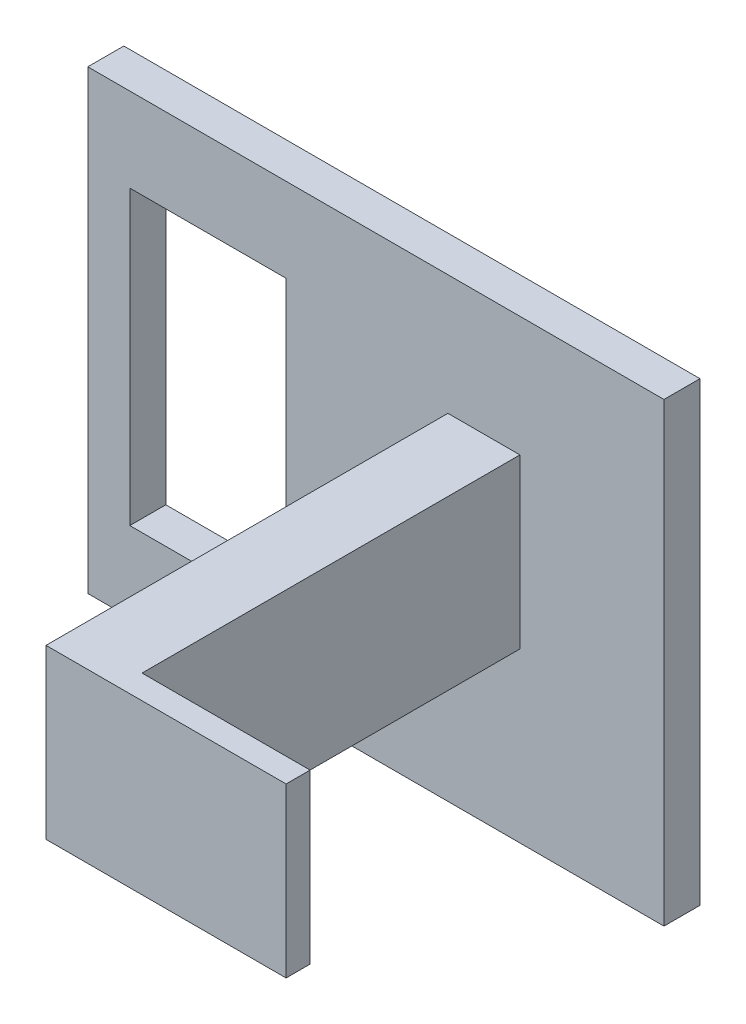
SolidWorks part; units mm, degrees
ref_plane "Front Plane" through (0, 0, 0) normal (0, 0, 1) x (1, 0, 0)
ref_plane "Top Plane" through (0, 0, 0) normal (0, 1, 0) x (1, 0, 0)
ref_plane "Right Plane" through (0, 0, 0) normal (1, 0, 0) x (0, 0, -1)
sketch "Sketch1" plane through (0, 0, 0) normal (0, 0, 1) x (1, 0, 0)
  line L1 (-70, 0) -> (-22, 0)
  line L2 (-70, 0) -> (-70, 38)
  line L3 (-70, 38) -> (-22, 38)
  line L4 (-22, 0) -> (-22, 38)
  line L6 (-66.5, 6.65) -> (-53.5, 6.65)
  line L7 (-66.5, 6.65) -> (-66.5, 31)
  line L8 (-66.5, 31) -> (-53.5, 31)
  line L9 (-53.5, 6.65) -> (-53.5, 31)
extrude "Servo_Shelf" add sketch "Sketch1" along normal blind 3 from offset 36.48
sketch "Sketch2" plane through (0, 0, 0) normal (0, 0, 1) x (1, 0, 0)
  line L1 (-40, 14) -> (-34, 14)
  line L2 (-40, 14) -> (-40, 28)
  line L3 (-40, 28) -> (-34, 28)
  line L4 (-34, 14) -> (-34, 28)
extrude "Outboard_Riser" add sketch "Sketch2" along normal blind 33.48 from offset 34.48
sketch "Sketch3" plane through (0, 0, 0) normal (0, 0, 1) x (1, 0, 0)
  line L1 (-40, 14) -> (-20, 14)
  line L2 (-40, 14) -> (-40, 28)
  line L3 (-40, 28) -> (-20, 28)
  line L4 (-20, 14) -> (-20, 28)
extrude "Plate_Attachment_Foot" add sketch "Sketch3" along normal blind 2 from offset 2
